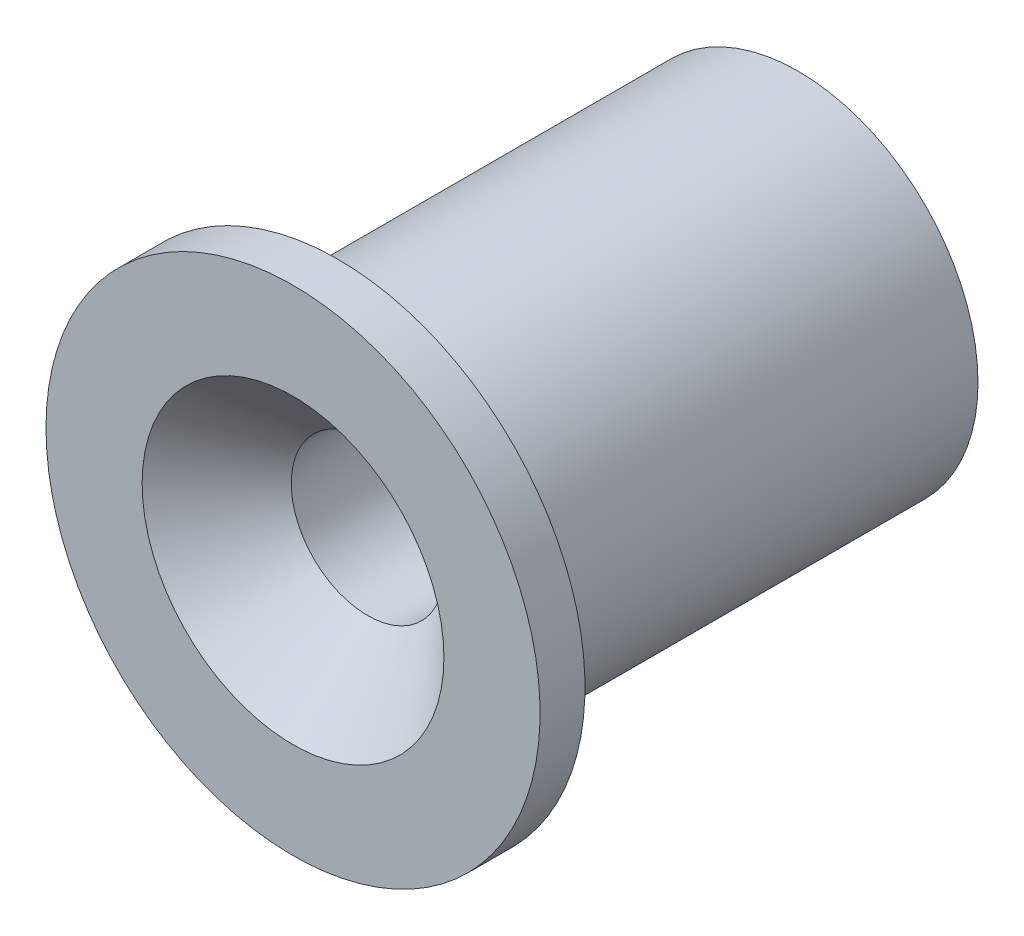
SolidWorks part; units mm, degrees
material "Bronce comercial, UNS C22000 (90-10 bronce)"
ref_plane "Alzado" through (0, 0, 0) normal (0, 0, 1) x (1, 0, 0)
ref_plane "Planta" through (0, 0, 0) normal (0, 1, 0) x (1, 0, 0)
ref_plane "Vista lateral" through (0, 0, 0) normal (1, 0, 0) x (0, 0, -1)
sketch "Croquis1" plane through (0, 0, 0) normal (0, 1, 0) x (1, 0, 0)
  line L0 (0, 19.1421) -> (0, -16.0355) construction
  line L1 (-1.5, 11.25) -> (-1.5, 0)
  line L2 (-1.5, 0) -> (-5.5, 0)
  line L3 (-5.5, 0) -> (-5.5, 1)
  line L4 (-5.5, 1) -> (-4, 1)
  line L5 (-4, 1) -> (-4, 11.25)
  line L6 (-4, 11.25) -> (-1.5, 11.25)
  dimension "D1" = 11.25
  dimension "D2" = 3
  dimension "D3" = 11
  dimension "D4" = 1
  dimension "D5" = 1.5
revolve "Revolución1" add sketch "Croquis1" angle 360 about L0
hole_wizard "Refrentado para tornillo tapón con cabeza plana de clavija de M31" positions "Croquis2" profile "Croquis3" countersink size "M3" standard "Ansi Metric" end condition through all
sketch "Croquis2" plane through (0, 0, 0) normal (0, 0, 1) x (1, 0, 0)
  point P0 (0, 0)
sketch "Croquis3" plane through (0, 0, 0) normal (1, 0, 0) x (0, -1, 0)
  line L0 (0, 0) -> (0, 11.25)
  line L1 (0, 11.25) -> (1.7, 11.25)
  line L2 (1.7, 11.25) -> (1.7, 1.66)
  line L3 (1.7, 1.66) -> (3.36, 0)
  line L5 (3.36, 0) -> (0, 0)
  line L6 (-1.7, 1.66) -> (-3.36, 0) construction
  line L11 (0, -6.35) -> (0, 107.95) construction
  dimension "Diámetro de taladro hasta el siguiente" = 3.4
  dimension "Profundidad de taladro hasta el siguiente" = 11.25
  dimension "Diámetro de avellanado cercano" = 6.72
  dimension "Ángulo de avellanado cercano" = 90
